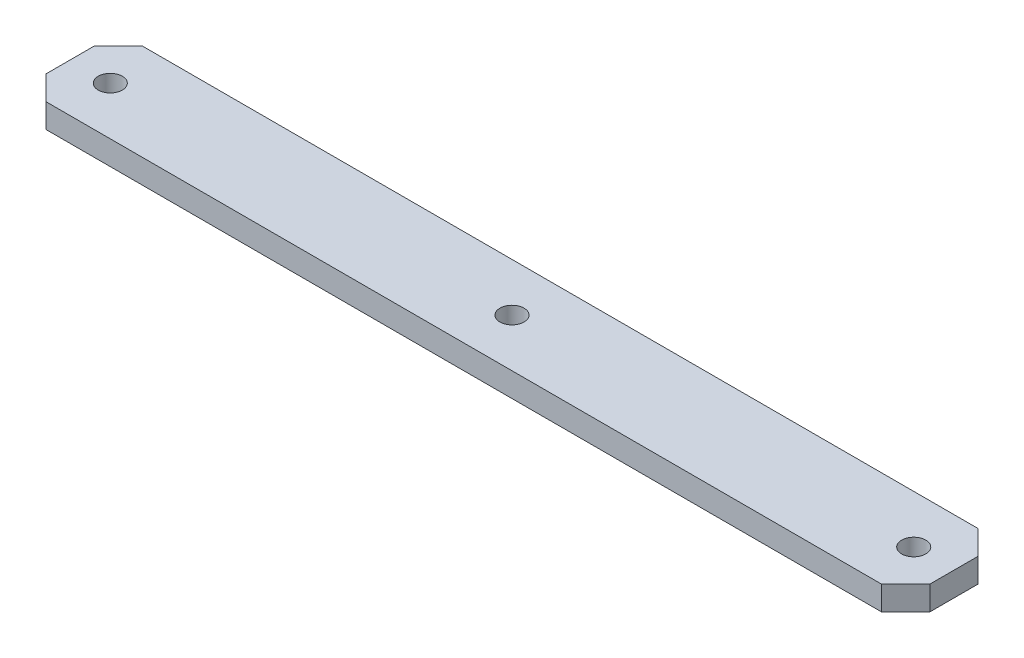
SolidWorks part; units mm, degrees
ref_plane "Front Plane" through (0, 0, 0) normal (0, 0, 1) x (1, 0, 0)
ref_plane "Top Plane" through (0, 0, 0) normal (0, 1, 0) x (1, 0, 0)
ref_plane "Right Plane" through (0, 0, 0) normal (1, 0, 0) x (0, 0, -1)
sketch "Sketch1" plane through (0, 0, 0) normal (0, 1, 0) x (1, 0, 0)
  line L0 (-55, 3) -> (-52, 6)
  line L1 (-52, 6) -> (52, 6)
  line L2 (-55, 3) -> (-55, -3)
  line L3 (-52, -6) -> (52, -6)
  line L4 (55, 3) -> (55, -3)
  line L5 (-55, 6) -> (55, -6) construction
  line L6 (-55, -6) -> (55, 6) construction
  line L7 (-55, -3) -> (-52, -6)
  line L8 (52, 6) -> (55, 3)
  line L9 (52, -6) -> (55, -3)
  circle A0 centre (-50, 0) radius 1.5
  circle A1 centre (0, 0) radius 1.5
  circle A2 centre (50, 0) radius 1.5
  point P0 (0, 0)
  dimension "D3" = 3
  dimension "D1" = 110
  dimension "D2" = 12
  dimension "D4" = 5
  dimension "D10" = 5
extrude "Boss-Extrude1" add sketch "Sketch1" along normal blind 3 contours A0 | L8 L4 L9 L3 L7 L2 L0 L1 | A1 | A2
